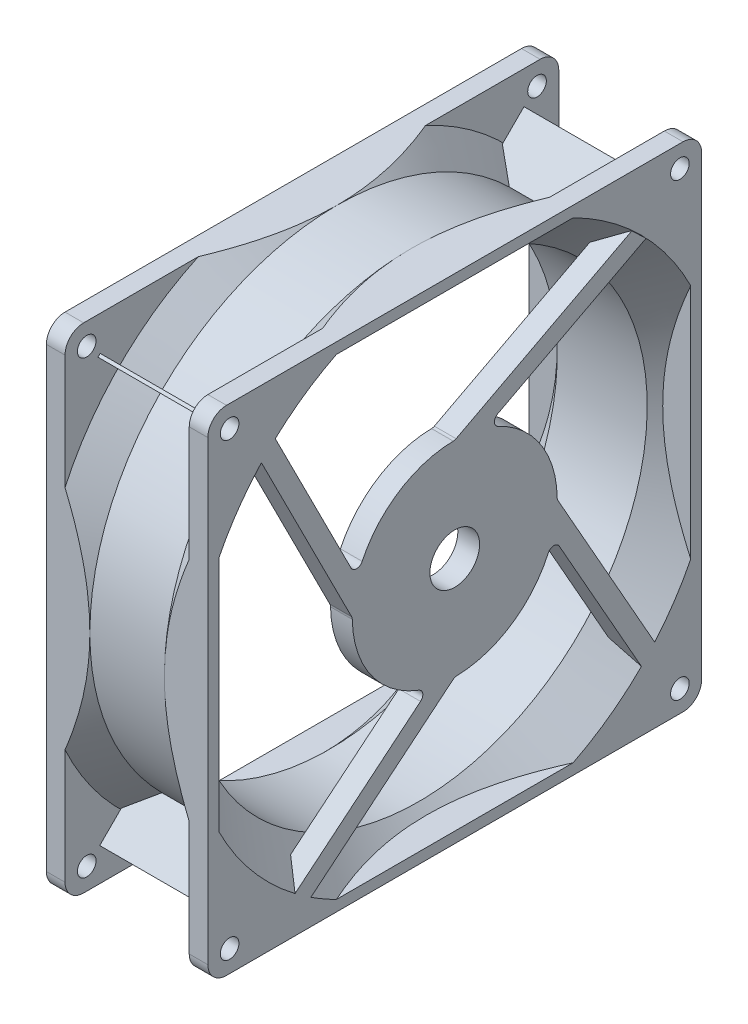
SolidWorks part; units mm, degrees
material "ABS"
ref_plane "Front Plane" through (0, 0, 0) normal (0, 0, 1) x (1, 0, 0)
ref_plane "Top Plane" through (0, 0, 0) normal (0, 1, 0) x (1, 0, 0)
ref_plane "Right Plane" through (0, 0, 0) normal (1, 0, 0) x (0, 0, -1)
sketch "Sketch1" plane through (0, 0, 0) normal (0, 0, 1) x (1, 0, 0)
  line L0 (0, 0) -> (0, 39.75) construction
  line L1 (-6, 39.75) -> (6, 39.75)
  line L2 (6, 39.75) -> (10, 43.75)
  line L3 (10, 43.75) -> (10, 62.6656)
  line L4 (-10, 43.75) -> (-10, 62.6656)
  line L5 (-6, 39.75) -> (-10, 43.75)
  line L6 (13, 42.5074) -> (13, 62.6656)
  line L7 (7.2426, 36.75) -> (13, 42.5074)
  line L8 (-7.2426, 36.75) -> (7.2426, 36.75)
  line L9 (-7.2426, 36.75) -> (-13, 42.5074)
  line L10 (-13, 42.5074) -> (-13, 62.6656)
  line L11 (-13, 62.6656) -> (-10, 62.6656)
  line L12 (10, 62.6656) -> (13, 62.6656)
  line L13 (0, 0) -> (31.1204, 0) construction
  dimension "D1" = 135
  dimension "D2" = 6
  dimension "D3" = 4
  dimension "D4" = 18.9156
  dimension "D5" = 20
  dimension "D7" = 39.75
  dimension "D6" = 3
revolve "Revolve1" add sketch "Sketch1" angle 360 about L13
sketch "Sketch2" plane through (0, 0, 0) normal (1, 0, 0) x (0, 0, -1)
  line L1 (39.75, -39.75) -> (-39.75, -39.75)
  line L2 (39.75, -39.75) -> (39.75, 39.75)
  line L3 (39.75, 39.75) -> (-39.75, 39.75)
  line L4 (-39.75, -39.75) -> (-39.75, 39.75)
  line L5 (39.75, -39.75) -> (-39.75, 39.75) construction
  line L6 (39.75, 39.75) -> (-39.75, -39.75) construction
  line L7 (77.5154, -71.9672) -> (-77.5154, -71.9672)
  line L8 (77.5154, -71.9672) -> (77.5154, 71.9672)
  line L9 (77.5154, 71.9672) -> (-77.5154, 71.9672)
  line L10 (-77.5154, -71.9672) -> (-77.5154, 71.9672)
  line L11 (77.5154, -71.9672) -> (-77.5154, 71.9672) construction
  line L12 (77.5154, 71.9672) -> (-77.5154, -71.9672) construction
  point P0 (0, 0)
  point P6 (0, 0)
  dimension "D1" = 79.5
  dimension "D2" = 77.5154
  dimension "D3" = 71.9672
extrude "Cut-Extrude1" cut sketch "Sketch2" against normal through all and the other way through all
sketch "Sketch4" plane through (-13, 0, 0) normal (-1, 0, 0) x (0, 0, 1)
  line L0 (-16.1696, 39.75) -> (19.1891, 39.75)
  line L1 (-39.75, 39.75) -> (-15.0603, 39.75) construction
  line L2 (15.0603, 39.75) -> (39.75, 39.75) construction
  line L4 (19.1891, 39.75) -> (20.0515, 37.9965)
  line L5 (20.0515, 37.9965) -> (-20.6733, 37.9965)
  line L6 (-20.6733, 37.9965) -> (-16.1696, 39.75)
  line L7 (39.75, 39.75) -> (39.75, 15.0603) construction
  dimension "D1" = 19.6985
  dimension "D2" = 20.5609
  dimension "D3" = 55.9196
  dimension "D4" = 60.4233
  dimension "D5" = 1.7535
extrude "Boss-Extrude1" add sketch "Sketch4" against normal up to next
pattern_circular "CirPattern1" count 4 over 360 about axis through (0, 0, 0) along (1, 0, 0) of "Boss-Extrude1"
mirror "Mirror1" about plane through (0, 0, 0) normal (1, 0, 0) of "CirPattern1", "Boss-Extrude1"
ref_plane "Plane1" through (0, 0, 0) normal (0, 0.7071, 0.7071) x (-1, 0, 0)
sketch "Sketch5" plane through (0, 0, 0) normal (0, 0.7071, 0.7071) x (-1, 0, 0)
  line L0 (-32.2415, 48.5) -> (43.5859, 48.5) construction
  line L1 (10, 0) -> (6, 0) construction
  dimension "D1" = 48.5
ref_plane "Plane2" through (0, -34.2947, 34.2947) normal (0, 0.7071, -0.7071) x (-1, 0, 0)
sketch "Sketch6" plane through (0, -34.2947, 34.2947) normal (0, 0.7071, -0.7071) x (-1, 0, 0)
  line L1 (9.8305, 0.0501) -> (-10.9661, 0.0501)
  line L2 (9.8305, 0.0501) -> (9.8305, -0.4499)
  line L3 (9.8305, -0.4499) -> (-10.9661, -0.4499)
  line L4 (-10.9661, 0.0501) -> (-10.9661, -0.4499)
  dimension "D1" = 0.5
  dimension "D2" = 9.8305
  dimension "D3" = 10.9661
  dimension "D4" = 0.0501
extrude "Boss-Extrude2" add sketch "Sketch6" along normal up to next
pattern_circular "CirPattern2" count 4 over 360 about axis through (0, 0, 0) along (1, 0, 0) of "Boss-Extrude2"
sketch "Sketch8" plane through (-13, 0, 0) normal (-1, 0, 0) x (0, 0, 1)
  line L0 (39.75, 39.75) -> (39.75, -39.75) construction
  line L2 (39.75, -39.75) -> (-39.75, -39.75) construction
  circle A0 centre (36.25, -36.25) radius 1.5
  dimension "D1" = 3
  dimension "D2" = 3.5
  dimension "D3" = 3.5
extrude "Cut-Extrude2" cut sketch "Sketch8" against normal through all
fillet "Fillet1" radius 3 2 edges at (11.5, -39.75, 39.75) (-11.5, -39.75, 39.75)
pattern_circular "CirPattern5" count 4 over 360 about axis through (0, 0, 0) along (1, 0, 0) of "Cut-Extrude2"
fillet "Fillet2" radius 3 2 edges at (11.5, 39.75, 39.75) (-11.5, 39.75, 39.75)
fillet "Fillet3" radius 3 1 edges at (-11.5, 39.75, -39.75)
fillet "Fillet4" radius 3 1 edges at (-11.5, -39.75, -39.75)
sketch "Sketch9" plane through (13, 0, 0) normal (1, 0, 0) x (0, 0, -1)
  line L0 (0, 0) -> (0, 16.5) construction
  line L1 (0.2146, 16.6125) -> (28.5207, 31.448)
  line L2 (30.7935, 29.2521) -> (6.9319, 16.746)
  line L3 (-0.2727, -16.7253) -> (-23.1669, -35.6394)
  line L4 (-25.7111, -33.8499) -> (-5.5059, -17.1574)
  line L5 (16.6276, -0.2255) -> (32.1991, -27.7506)
  line L6 (30.0572, -30.0572) -> (16.8327, -6.6808)
  line L7 (-31.1316, 28.9431) -> (-16.6059, 0.2095)
  line L8 (-28.8977, 31.1737) -> (-16.7029, 7.0509)
  line L9 (-16.5, 0) -> (16.5, 0) construction
  line L10 (19.0562, 37.9965) -> (-19.0562, 37.9965) construction
  line L11 (-8.9179, 13.8824) -> (9.1063, -13.7596) construction
  line L12 (28.5207, 31.448) -> (30.7935, 29.2521)
  arc A0 (16.4981, 0.2516) -> (6.9734, 14.954) centre (0, 0) ccw
  arc A2 (19.0562, -37.9965) -> (37.9965, -19.0562) centre (0, 0) ccw construction
  arc A3 (-37.9965, -19.0562) -> (-19.0562, -37.9965) centre (0, 0) ccw construction
  arc A4 (-19.0562, 37.9965) -> (-37.9965, 19.0562) centre (0, 0) ccw construction
  arc A5 (30.0572, -30.0572) -> (32.1991, -27.7506) centre (0, 0) ccw
  arc A6 (-25.7111, -33.8499) -> (-23.1669, -35.6394) centre (0, 0) ccw
  arc A7 (-28.8977, 31.1737) -> (-31.1316, 28.9431) centre (0, 0) ccw
  arc A9 (-0.2353, 16.4983) -> (-14.907, 7.0733) centre (0, 0) ccw
  arc A10 (-16.4984, -0.2279) -> (-5.7918, -15.4501) centre (0, 0) ccw
  arc A11 (0.3434, -16.4964) -> (15.0502, -6.7633) centre (0, 0) ccw
  arc A12 (-0.2353, 16.4983) -> (0.2146, 16.6125) centre (-0.2496, 17.4982) ccw
  arc A13 (6.9734, 14.954) -> (6.9319, 16.746) centre (7.3961, 15.8603) cw
  arc A14 (16.4981, 0.2516) -> (16.6276, -0.2255) centre (17.498, 0.2669) ccw
  arc A15 (16.8327, -6.6808) -> (15.0502, -6.7633) centre (15.9623, -7.1732) ccw
  arc A16 (-5.5059, -17.1574) -> (-5.7918, -15.4501) centre (-6.1428, -16.3864) ccw
  arc A17 (-0.2727, -16.7253) -> (0.3434, -16.4964) centre (0.3642, -17.4962) cw
  arc A18 (-16.7029, 7.0509) -> (-14.907, 7.0733) centre (-15.8104, 7.502) ccw
  arc A19 (-16.4984, -0.2279) -> (-16.6059, 0.2095) centre (-17.4983, -0.2417) ccw
  point P38 (-4.0876, -15.9857)
  point P41 (0, -16.5)
  point P44 (-15.7016, 5.0703)
  dimension "D1" = 33
  dimension "D6" = 1
  dimension "D2" = 3
  dimension "D3" = 3
  dimension "D4" = 3
  dimension "D5" = 3
  dimension "D7" = 1.5579
  dimension "D8" = 12.9133
  dimension "D9" = 18.8066
  dimension "D10" = 34.1064
  dimension "D32" = 47.5768
  dimension "D34" = 49.8497
extrude "Boss-Extrude3" add sketch "Sketch9" against normal blind 3.5
sketch "Sketch10" plane through (13, 0, 0) normal (1, 0, 0) x (0, 0, -1)
  circle A0 centre (0, 0) radius 4
  dimension "D1" = 8
extrude "Cut-Extrude3" cut sketch "Sketch10" against normal through all
sketch "Sketch12" plane through (0, -39.75, 0) normal (0, -1, 0) x (1, 0, 0)
  line L0 (-13, 0) -> (13, 0.2727) construction
  line L1 (-13, 36.75) -> (-13, -36.75) construction
  line L2 (-10, 18.2757) -> (-10, 39.75) construction
  line L3 (-10, 13.7727) -> (10, 13.7727)
  line L4 (-10, 13.7727) -> (-10, -13.2273)
  line L5 (-10, -13.2273) -> (10, -13.2273)
  line L6 (10, 13.7727) -> (10, -13.2273)
  line L7 (10, -18.2757) -> (10, -36.75) construction
  point P13 (0, 0)
  dimension "D1" = 13.5
  dimension "D2" = 13.5
extrude "Boss-Extrude4" add sketch "Sketch12" against normal up to next
